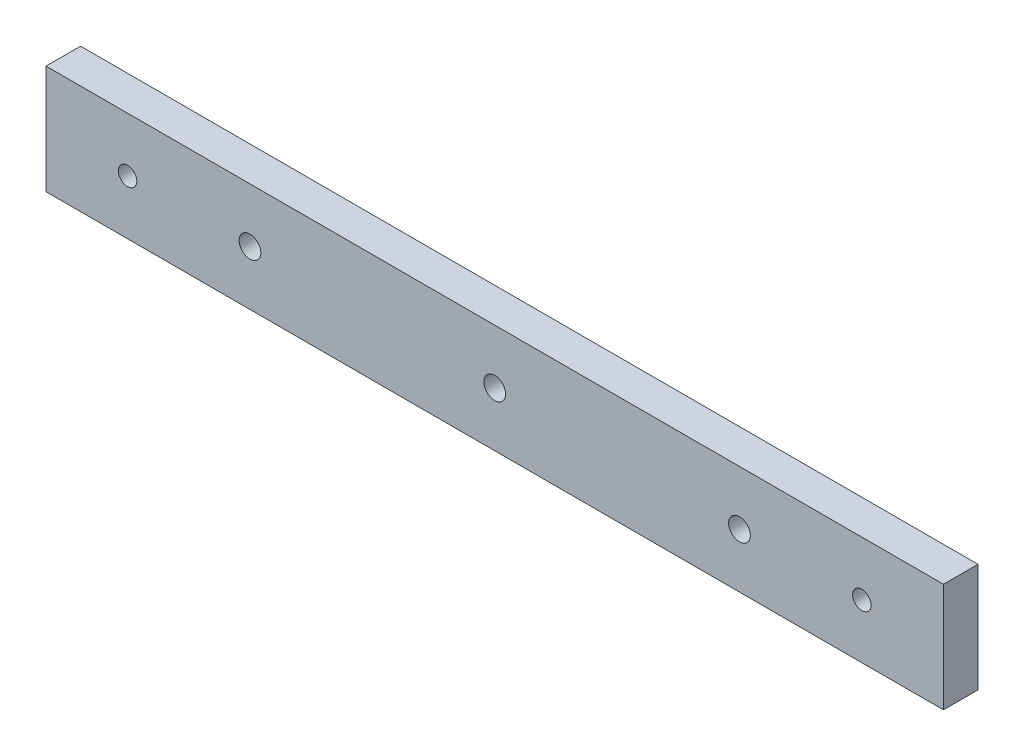
SolidWorks part; units mm, degrees
ref_plane "Front" through (0, 0, 0) normal (0, 0, 1) x (1, 0, 0)
ref_plane "Top" through (0, 0, 0) normal (0, 1, 0) x (1, 0, 0)
ref_plane "Right" through (0, 0, 0) normal (1, 0, 0) x (0, 0, -1)
sketch "Sketch1" plane through (0, 0, 0) normal (0, 0, 1) x (-1, 0, 0)
  line L0 (135.4523, 2.5754) -> (135.4523, 22.5754)
  line L1 (135.4523, 2.5754) -> (-29.5477, 2.5754)
  line L2 (135.4523, 22.5754) -> (-29.5477, 22.5754)
  line L3 (-29.5477, 2.5754) -> (-29.5477, 22.5754)
  circle A0 centre (-14.5477, 12.5754) radius 1.7
  circle A1 centre (120.4523, 12.5754) radius 1.7
  dimension "D4" = 20
  dimension "D1" = 165
  dimension "D2" = 15
  dimension "D3" = 15
  dimension "D5" = 10
  dimension "D6" = 10
extrude "Boss-Extrude1" add sketch "Sketch1" along normal blind 6.35 contours L3 L1 L0 L2 A1 A0
sketch "Sketch3" plane through (0, 0, 0) normal (0, 0, -1) x (-1, 0, 0)
  line L0 (120.4523, -12.5754) -> (-14.5477, -12.5754)
  line L1 (120.4523, -12.5754) -> (75.4523, -12.5754)
  line L2 (75.4523, -12.5754) -> (30.4523, -12.5754)
  line L3 (30.4523, -12.5754) -> (-14.5477, -12.5754)
  line L4 (56.5023, -12.5754) -> (49.4023, -12.5754) construction
  line L5 (56.5023, -16.1254) -> (49.4023, -16.1254)
  line L6 (56.5023, -9.0254) -> (49.4023, -9.0254)
  line L7 (120.4523, -12.5754) -> (75.4523, -12.5754)
  line L8 (101.5023, -12.5754) -> (94.4023, -12.5754) construction
  line L9 (101.5023, -16.1254) -> (94.4023, -16.1254)
  line L10 (101.5023, -9.0254) -> (94.4023, -9.0254)
  line L11 (-14.5477, -12.5754) -> (30.4523, -12.5754)
  line L12 (11.5023, -12.5754) -> (4.4023, -12.5754) construction
  line L13 (11.5023, -16.1254) -> (4.4023, -16.1254)
  line L14 (11.5023, -9.0254) -> (4.4023, -9.0254)
  arc A0 (56.5023, -16.1254) -> (56.5023, -9.0254) centre (56.5023, -12.5754) ccw
  arc A1 (49.4023, -9.0254) -> (49.4023, -16.1254) centre (49.4023, -12.5754) ccw
  arc A2 (101.5023, -16.1254) -> (101.5023, -9.0254) centre (101.5023, -12.5754) ccw
  arc A3 (94.4023, -9.0254) -> (94.4023, -16.1254) centre (94.4023, -12.5754) ccw
  arc A4 (11.5023, -16.1254) -> (11.5023, -9.0254) centre (11.5023, -12.5754) ccw
  arc A5 (4.4023, -9.0254) -> (4.4023, -16.1254) centre (4.4023, -12.5754) ccw
  point P8 (52.9523, -12.5754)
  point P15 (97.9523, -12.5754)
  point P22 (7.9523, -12.5754)
  dimension "D3" = 3.55
  dimension "D6" = 3.55
  dimension "D8" = 3.55
  dimension "D1" = 45
  dimension "D2" = 45
  dimension "D4" = 7.1
  dimension "D5" = 7.1
  dimension "D7" = 7.1
extrude "Cut-Extrude2" cut sketch "Sketch3" against normal blind 3.35 contours L9 A3 L10 A2 | L5 A1 L6 A0 | L13 A5 L14 A4
sketch "Sketch4" plane through (0, 0, 3.35) normal (0, 0, -1) x (-1, 0, 0)
  line L0 (7.9523, -9.0254) -> (7.9523, -16.1254)
  line L1 (11.5023, -9.0254) -> (4.4023, -9.0254) construction
  line L2 (11.5023, -16.1254) -> (4.4023, -16.1254) construction
  line L3 (7.9523, -16.1254) -> (52.9523, -16.1254)
  line L4 (56.5023, -16.1254) -> (49.4023, -16.1254) construction
  line L5 (52.9523, -16.1254) -> (52.9523, -9.0254)
  line L6 (56.5023, -9.0254) -> (49.4023, -9.0254) construction
  line L7 (52.9523, -9.0254) -> (97.9523, -9.0254)
  line L8 (101.5023, -9.0254) -> (94.4023, -9.0254) construction
  line L9 (97.9523, -9.0254) -> (97.9523, -16.1254)
  line L10 (101.5023, -16.1254) -> (94.4023, -16.1254) construction
  circle A0 centre (97.9523, -12.5754) radius 2
  circle A1 centre (52.9523, -12.5754) radius 2
  circle A2 centre (7.9523, -12.5754) radius 2
extrude "Cut-Extrude3" cut sketch "Sketch4" against normal blind 3 contours L0 A2 | L0 A2 | L5 A1 | L5 A1 | L9 A0 | L9 A0
